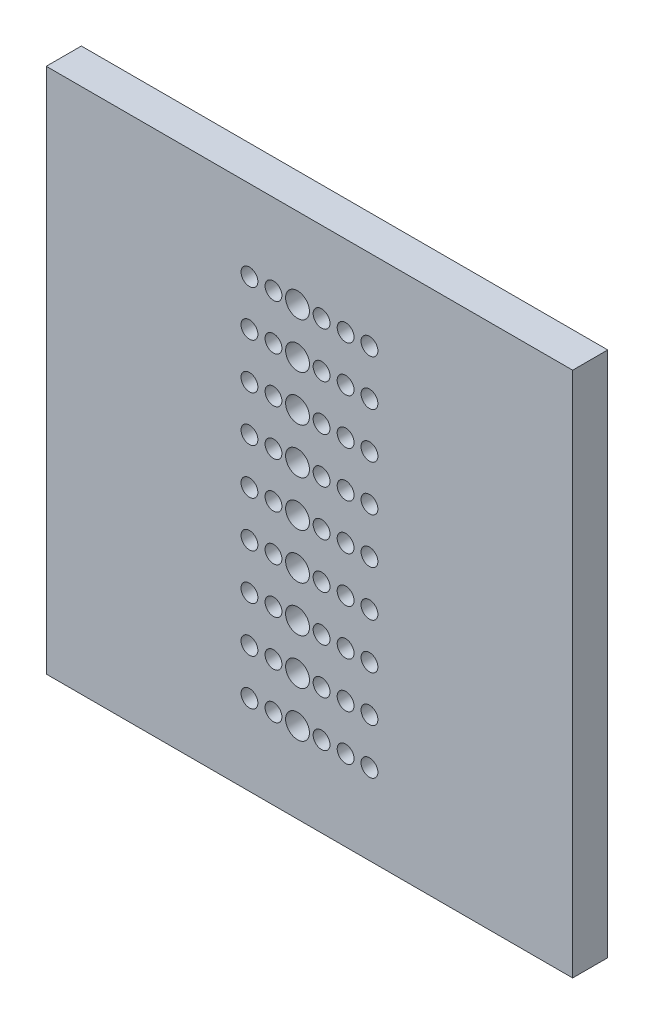
SolidWorks part; units mm, degrees
ref_plane "Plan de face" through (0, 0, 0) normal (0, 0, 1) x (1, 0, 0)
ref_plane "Plan de dessus" through (0, 0, 0) normal (0, 1, 0) x (1, 0, 0)
ref_plane "Plan de droite" through (0, 0, 0) normal (1, 0, 0) x (0, 0, -1)
sketch "Esquisse2" plane through (0, 0, 0) normal (0, 0, 1) x (1, 0, 0)
  line L1 (-15, -15) -> (15, -15)
  line L2 (-15, -15) -> (-15, 15)
  line L3 (-15, 15) -> (15, 15)
  line L4 (15, -15) -> (15, 15)
  line L5 (-15, -15) -> (15, 15) construction
  line L6 (-15, 15) -> (15, -15) construction
  point P0 (0, 0)
extrude "Boss.-Extru.1" add sketch "Esquisse2" along normal blind 2
sketch "Esquisse3" plane through (0, 0, 2) normal (0, 0, 1) x (1, 0, 0)
  circle A0 centre (-3.42, -10.4) radius 0.48
  circle A1 centre (-3.42, -7.8) radius 0.48
  circle A2 centre (-3.42, -5.2) radius 0.48
  circle A3 centre (-3.42, -2.6) radius 0.48
  circle A4 centre (-3.42, 0) radius 0.48
  circle A5 centre (-3.42, 2.6) radius 0.48
  circle A6 centre (-3.42, 5.2) radius 0.48
  circle A7 centre (-3.42, 7.8) radius 0.48
  circle A8 centre (-3.42, 10.4) radius 0.48
  circle A9 centre (-2.05, -10.4) radius 0.48
  circle A10 centre (-2.05, -7.8) radius 0.48
  circle A11 centre (-2.05, -5.2) radius 0.48
  circle A12 centre (-2.05, -2.6) radius 0.48
  circle A13 centre (-2.05, 0) radius 0.48
  circle A14 centre (-2.05, 2.6) radius 0.48
  circle A15 centre (-2.05, 5.2) radius 0.48
  circle A16 centre (-2.05, 7.8) radius 0.48
  circle A17 centre (-2.05, 10.4) radius 0.48
  circle A18 centre (-0.68, -10.4) radius 0.68
  circle A19 centre (-0.68, -7.8) radius 0.68
  circle A20 centre (-0.68, -5.2) radius 0.68
  circle A21 centre (-0.68, -2.6) radius 0.68
  circle A22 centre (-0.68, 0) radius 0.68
  circle A23 centre (-0.68, 2.6) radius 0.68
  circle A24 centre (-0.68, 5.2) radius 0.68
  circle A25 centre (-0.68, 7.8) radius 0.68
  circle A26 centre (-0.68, 10.4) radius 0.68
  circle A27 centre (0.69, -10.4) radius 0.48
  circle A28 centre (0.69, -7.8) radius 0.48
  circle A29 centre (0.69, -5.2) radius 0.48
  circle A30 centre (0.69, -2.6) radius 0.48
  circle A31 centre (0.69, 0) radius 0.48
  circle A32 centre (0.69, 2.6) radius 0.48
  circle A33 centre (0.69, 5.2) radius 0.48
  circle A34 centre (0.69, 7.8) radius 0.48
  circle A35 centre (0.69, 10.4) radius 0.48
  circle A36 centre (2.06, -10.4) radius 0.48
  circle A37 centre (2.06, -7.8) radius 0.48
  circle A38 centre (2.06, -5.2) radius 0.48
  circle A39 centre (2.06, -2.6) radius 0.48
  circle A40 centre (2.06, 0) radius 0.48
  circle A41 centre (2.06, 2.6) radius 0.48
  circle A42 centre (2.06, 5.2) radius 0.48
  circle A43 centre (2.06, 7.8) radius 0.48
  circle A44 centre (2.06, 10.4) radius 0.48
  circle A45 centre (3.42, -10.4) radius 0.48
  circle A46 centre (3.42, -7.8) radius 0.48
  circle A47 centre (3.42, -5.2) radius 0.48
  circle A48 centre (3.42, -2.6) radius 0.48
  circle A49 centre (3.42, 0) radius 0.48
  circle A50 centre (3.42, 2.6) radius 0.48
  circle A51 centre (3.42, 5.2) radius 0.48
  circle A52 centre (3.42, 7.8) radius 0.48
  circle A53 centre (3.42, 10.4) radius 0.48
extrude "Enlèv. mat.-Extru.1" cut sketch "Esquisse3" against normal blind 10
